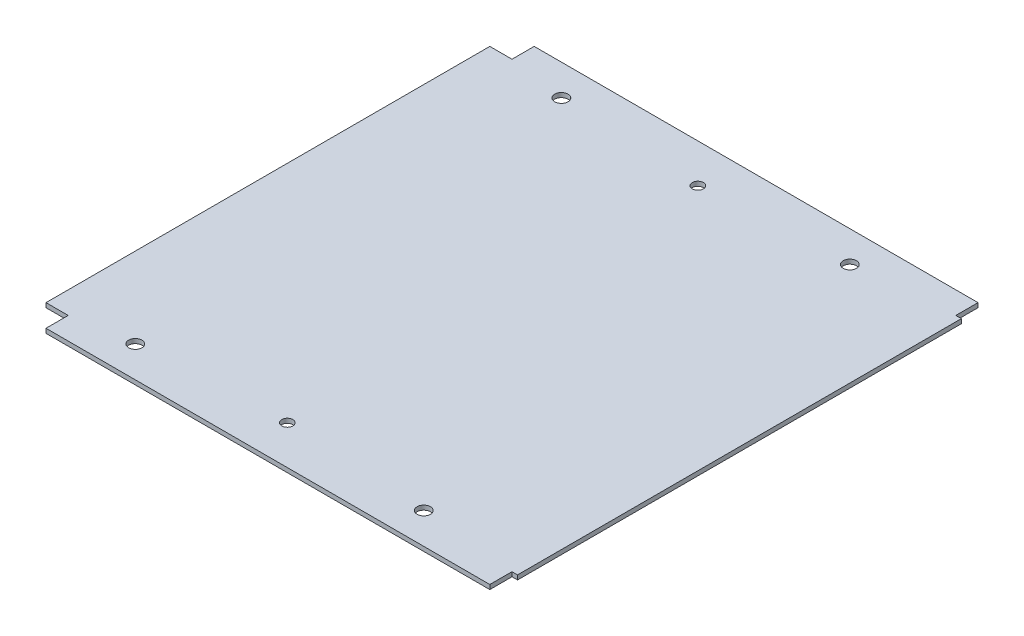
SolidWorks part; units mm, degrees
ref_plane "Front Plane" through (0, 0, 0) normal (0, 0, 1) x (1, 0, 0)
ref_plane "Top Plane" through (0, 0, 0) normal (0, 1, 0) x (1, 0, 0)
ref_plane "Right Plane" through (0, 0, 0) normal (1, 0, 0) x (0, 0, -1)
sketch "Sketch1" plane through (0, 0, 0) normal (0, 1, 0) x (1, 0, 0)
  line L1 (220, -220) -> (-220, -220)
  line L2 (220, -220) -> (220, 220)
  line L3 (220, 220) -> (-220, 220)
  line L4 (-220, -220) -> (-220, 220)
  line L5 (220, -220) -> (-220, 220) construction
  line L6 (220, 220) -> (-220, -220) construction
  point P0 (0, 0)
  dimension "D1" = 440
  dimension "D2" = 440
extrude "Boss-Extrude1" add sketch "Sketch1" along normal blind 4
sketch "Sketch2" plane through (0, 4, 0) normal (0, 1, 0) x (1, 0, 0)
  line L0 (220, 220) -> (-220, 220) construction
  line L1 (-45.5, 139.5) -> (45.5, 139.5)
  line L2 (-45.5, 139.5) -> (-45.5, 220)
  line L3 (-45.5, 220) -> (45.5, 220)
  line L4 (45.5, 139.5) -> (45.5, 220)
  line L9 (-154.5, -104.5) -> (-220, -104.5)
  line L10 (-154.5, -104.5) -> (-154.5, -220)
  line L11 (-154.5, -220) -> (-220, -220)
  line L12 (-220, -104.5) -> (-220, -220)
  line L14 (220, -220) -> (220, 220) construction
  line L15 (154.5, -104.5) -> (220, -104.5)
  line L16 (154.5, -104.5) -> (154.5, -220)
  line L17 (154.5, -220) -> (220, -220)
  line L18 (220, -104.5) -> (220, -220)
sketch "Sketch3" plane through (0, 4, 0) normal (0, 1, 0) x (1, 0, 0)
  line L1 (-220, -220) -> (-200, -220)
  line L2 (-220, -220) -> (-220, -200)
  line L3 (-220, -200) -> (-200, -200)
  line L4 (-200, -220) -> (-200, -200)
  line L5 (220, -220) -> (200, -220)
  line L6 (220, -220) -> (220, -200)
  line L7 (220, -200) -> (200, -200)
  line L8 (200, -220) -> (200, -200)
  line L9 (220, 220) -> (200, 220)
  line L10 (220, 220) -> (220, 200)
  line L11 (220, 200) -> (200, 200)
  line L12 (200, 220) -> (200, 200)
  line L13 (-220, 220) -> (-200, 220)
  line L14 (-220, 220) -> (-220, 200)
  line L15 (-220, 200) -> (-200, 200)
  line L16 (-200, 220) -> (-200, 200)
  dimension "D1" = 20
extrude "Cut-Extrude1" cut sketch "Sketch3" against normal blind 10
sketch "Sketch4" plane through (0, 4, 0) normal (0, 1, 0) x (1, 0, 0)
  line L0 (-147.5, 192) -> (112.5, 192) construction
  line L1 (-17.5, 185) -> (-17.5, 192) construction
  line L2 (-147.5, 192) -> (-147.5, -192) construction
  line L3 (-147.5, -192) -> (112.5, -192) construction
  line L4 (-17.5, -192) -> (-17.5, -185) construction
  line L5 (0, 0) -> (-147.5, 0) construction
  line L7 (-220, 200) -> (-200, 200) construction
  line L8 (-200, 200) -> (-200, 220) construction
  circle A0 centre (-147.5, 192) radius 6
  circle A1 centre (112.5, 192) radius 6
  circle A2 centre (-17.5, 185) radius 5
  circle A3 centre (112.5, -192) radius 6
  circle A4 centre (-17.5, -185) radius 5
  circle A5 centre (-147.5, -192) radius 6
  dimension "D1" = 12
  dimension "D2" = 10
  dimension "D4" = 7
  dimension "D3" = 260
  dimension "D5" = 8
  dimension "D6" = 52.5
extrude "Cut-Extrude2" cut sketch "Sketch4" against normal blind 10
sketch "Sketch5" plane through (0, 4, 0) normal (0, 1, 0) x (1, 0, 0)
  line L0 (220, -200) -> (200, -200) construction
  line L1 (220, 200) -> (205, 200)
  line L2 (220, 200) -> (220, -200)
  line L3 (220, -200) -> (205, -200)
  line L4 (205, 200) -> (205, -200)
  dimension "D1" = 15
extrude "Cut-Extrude3" cut sketch "Sketch5" against normal through all
